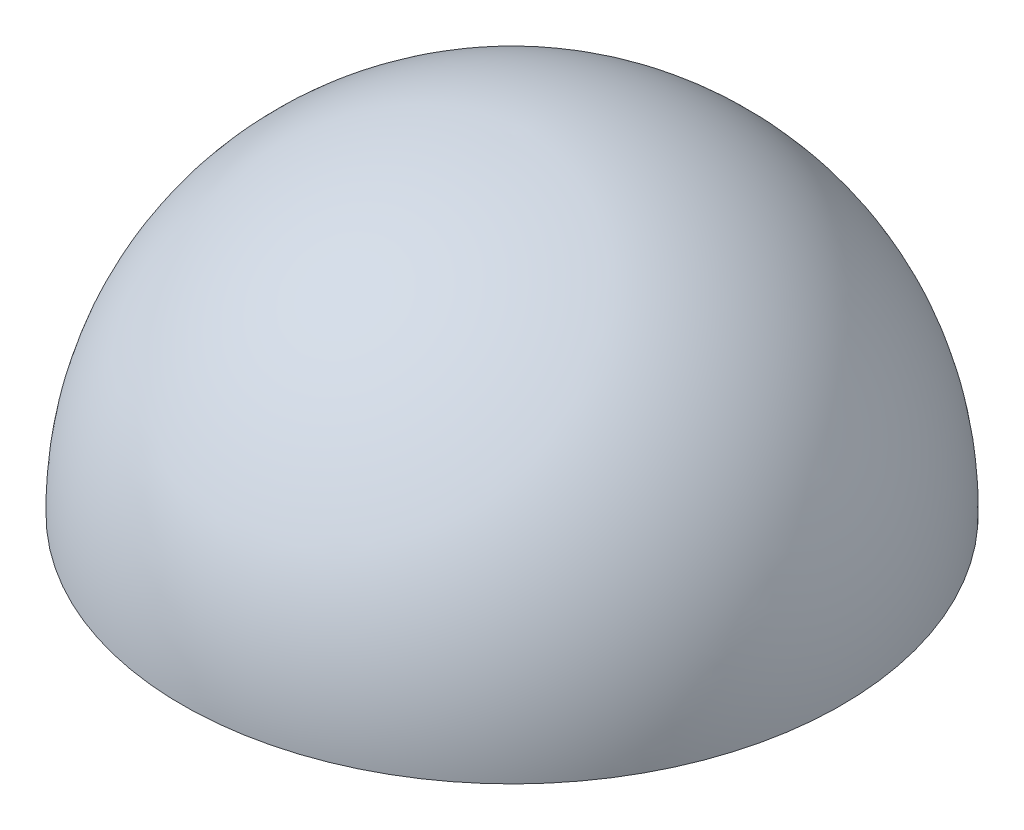
SolidWorks part; units mm, degrees
ref_plane "Front Plane" through (0, 0, 0) normal (0, 0, 1) x (1, 0, 0)
ref_plane "Top Plane" through (0, 0, 0) normal (0, 1, 0) x (1, 0, 0)
ref_plane "Right Plane" through (0, 0, 0) normal (1, 0, 0) x (0, 0, -1)
sketch "Sketch1" plane through (0, 0, 0) normal (0, 0, 1) x (1, 0, 0)
  line L0 (0, 0) -> (0, 4)
  line L1 (0, 0) -> (4, 0)
  arc A0 (4, 0) -> (0, 4) centre (0.0592, 0.0592) ccw
  dimension "D1" = 4
  dimension "D2" = 4
revolve "Revolve1" add sketch "Sketch1" angle 360 about L0
